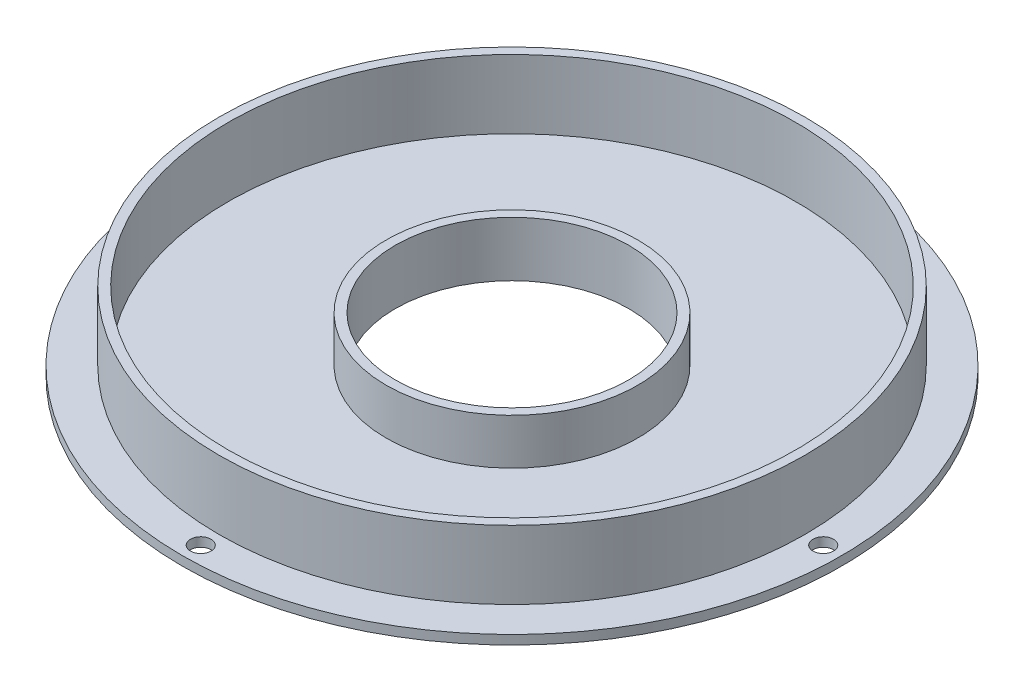
SolidWorks part; units mm, degrees
ref_plane "Front Plane" through (0, 0, 0) normal (0, 0, 1) x (1, 0, 0)
ref_plane "Top Plane" through (0, 0, 0) normal (0, 1, 0) x (1, 0, 0)
ref_plane "Right Plane" through (0, 0, 0) normal (1, 0, 0) x (0, 0, -1)
sketch "Sketch1" plane through (0, 0, 0) normal (0, 1, 0) x (1, 0, 0)
  circle A0 centre (0, 0) radius 72
  circle A1 centre (68, 0) radius 2.25
  circle A2 centre (0, -68) radius 2.25
  circle A3 centre (-68, 0) radius 2.25
  circle A4 centre (0, 68) radius 2.25
  circle A5 centre (0, 0) radius 25.5
  dimension "D1" = 144
  dimension "D2" = 4.5
  dimension "D5" = 51
  dimension "D3" = 68
  dimension "D4" = 4
extrude "Boss-Extrude1" add sketch "Sketch1" along normal blind 2
sketch "Sketch2" plane through (0, 2, 0) normal (0, 1, 0) x (1, 0, 0)
  circle A0 centre (0, 0) radius 25.5 construction
  circle A1 centre (0, 0) radius 25.5
  circle A2 centre (0, 0) radius 27.5
  dimension "D1" = 2
extrude "Boss-Extrude2" add sketch "Sketch2" along normal blind 10
sketch "Sketch3" plane through (0, 2, 0) normal (0, 1, 0) x (1, 0, 0)
  circle A1 centre (0, 0) radius 62
  circle A2 centre (0, 0) radius 64
  circle A3 centre (0, 0) radius 64
  dimension "D1" = 8
  dimension "D2" = 2
extrude "Boss-Extrude3" add sketch "Sketch3" along normal blind 15 contours A3
